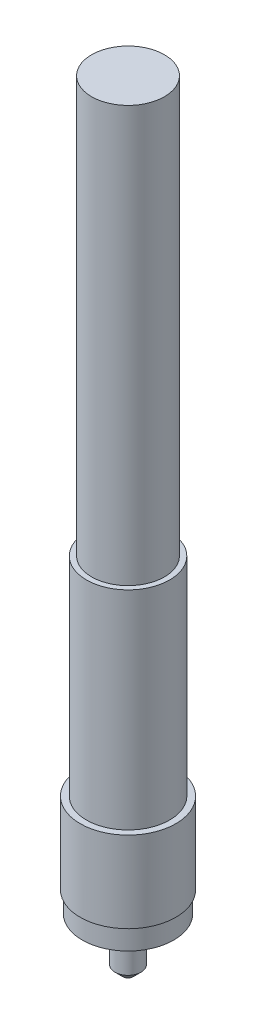
SolidWorks part; units mm, degrees
material "铸造合金钢"
ref_plane "前视基准面" through (0, 0, 0) normal (0, 0, 1) x (1, 0, 0)
ref_plane "上视基准面" through (0, 0, 0) normal (0, 1, 0) x (1, 0, 0)
ref_plane "右视基准面" through (0, 0, 0) normal (1, 0, 0) x (0, 0, -1)
sketch "草图1" plane through (0, 0, 0) normal (0, 1, 0) x (1, 0, 0)
  circle A0 centre (0, 0) radius 4.6
  dimension "D1" = 9.2
extrude "拉伸1" add sketch "草图1" along normal blind 9.8
sketch "草图2" plane through (0, 0, 0) normal (0, -1, 0) x (1, 0, 0)
  circle A0 centre (0, 0) radius 4.6 construction
  circle A1 centre (0, 0) radius 4.4
  circle A2 centre (0, 0) radius 4.6
  dimension "D1" = 0.2
extrude "切除-拉伸1" cut sketch "草图2" against normal blind 2
sketch "草图3" plane through (0, 0, 0) normal (0, -1, 0) x (1, 0, 0)
  circle A0 centre (0, 0) radius 3.9
  circle A1 centre (0, 0) radius 2.9
  dimension "D1" = 5.8
  dimension "D2" = 1
extrude "切除-拉伸2" cut sketch "草图3" against normal blind 4
sketch "草图4" plane through (0, 0, 0) normal (0, -1, 0) x (1, 0, 0)
  circle A1 centre (0, 0) radius 2.4
  dimension "D1" = 4.8
extrude "切除-拉伸3" cut sketch "草图4" against normal blind 5
sketch "草图5" plane through (0, 5, 0) normal (0, -1, 0) x (1, 0, 0)
  circle A0 centre (0, 0) radius 1.25
  dimension "D1" = 2.5
extrude "拉伸4" add sketch "草图5" along normal blind 10
chamfer "倒角1" distance 0.75 angle 45 1 edges at (0, -5, -1.25)
sketch "草图6" plane through (0, 0, 0) normal (0, -1, 0) x (1, 0, 0)
  circle A0 centre (0, 0) radius 2.4 construction
  circle A1 centre (0, 0) radius 2.9 construction
  circle A2 centre (0, 0) radius 2.4
  circle A3 centre (0, 0) radius 2.9
extrude "拉伸5" add sketch "草图6" along normal blind 1
sketch "草图7" plane through (0, 9.8, 0) normal (0, 1, 0) x (-1, 0, 0)
  circle A0 centre (0, 0) radius 4
  dimension "D1" = 8
extrude "拉伸6" add sketch "草图7" along normal blind 20
sketch "草图8" plane through (0, 29.8, 0) normal (0, 1, 0) x (-1, 0, 0)
  circle A0 centre (0, 0) radius 3.5
  dimension "D1" = 7
extrude "拉伸7" add sketch "草图8" along normal blind 40
